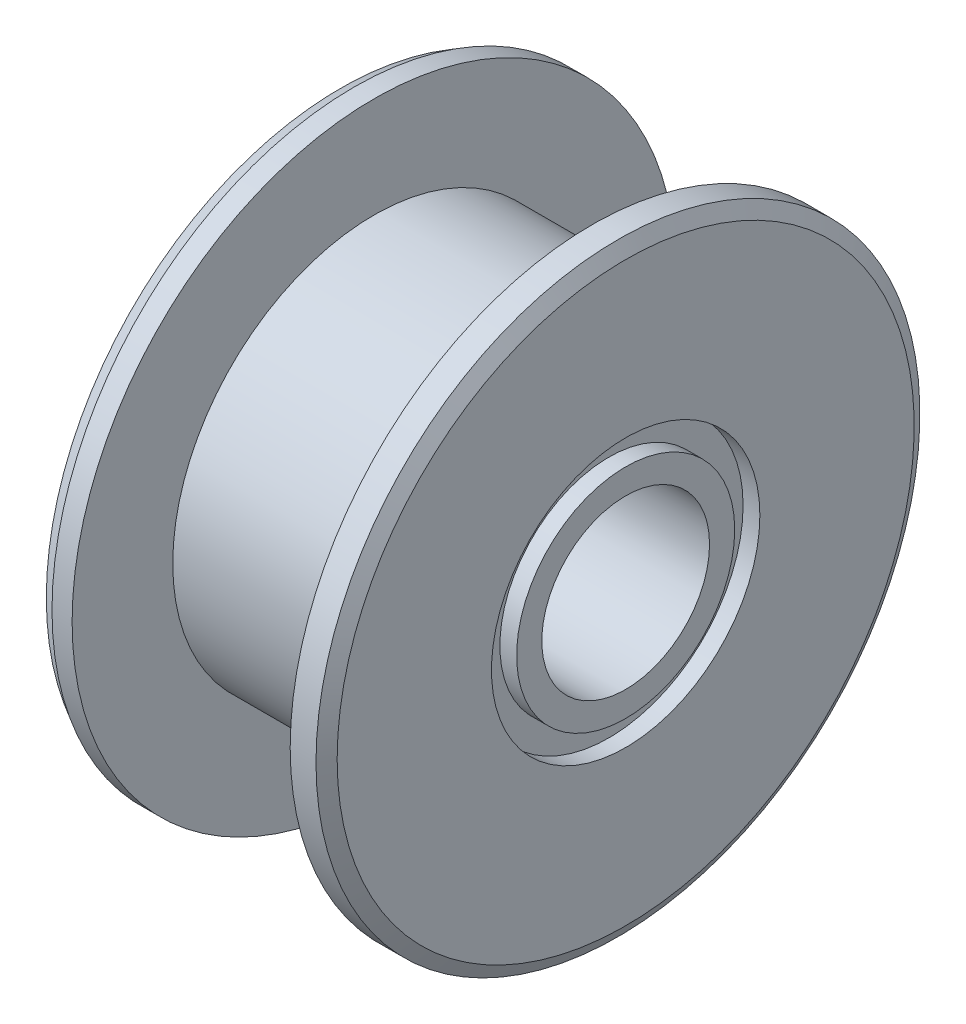
SolidWorks part; units mm, degrees
ref_plane "Front Plane" through (0, 0, 0) normal (0, 0, 1) x (1, 0, 0)
ref_plane "Top Plane" through (0, 0, 0) normal (0, 1, 0) x (1, 0, 0)
ref_plane "Right Plane" through (0, 0, 0) normal (1, 0, 0) x (0, 0, -1)
sketch "Sketch1" plane through (0, 0, 0) normal (0, 0, 1) x (1, 0, 0)
  line L0 (0, 0) -> (8.5, 0) construction
  line L1 (0, 0) -> (0, 9)
  line L2 (0, 9) -> (1, 9)
  line L3 (1, 9) -> (1, 6)
  line L4 (1, 6) -> (7.5, 6)
  line L5 (7.5, 6) -> (7.5, 9)
  line L6 (7.5, 9) -> (8.5, 9)
  line L7 (8.5, 9) -> (8.5, 0)
  line L8 (0, 0) -> (8.5, 0)
  dimension "D1" = 8.5
  dimension "D2" = 18
  dimension "D3" = 12
  dimension "D4" = 6.5
revolve "Revolve1" add sketch "Sketch1" angle 360 about L0
chamfer "Chamfer1" distance 0.4 angle 30 2 edges at (0, 0, 9) (8.5, 0, 9)
sketch "Sketch2" plane through (8.5, 0, 0) normal (1, 0, 0) x (0, 0, -1)
  circle A0 centre (0, 0) radius 2.5
  dimension "D1" = 5
extrude "Cut-Extrude1" cut sketch "Sketch2" against normal through all
sketch "Sketch3" plane through (8.5, 0, 0) normal (1, 0, 0) x (0, 0, -1)
  circle A0 centre (0, 0) radius 3.25
  circle A1 centre (0, 0) radius 4
  dimension "D1" = 8
  dimension "D2" = 6.5
extrude "Cut-Extrude2" cut sketch "Sketch3" against normal blind 0.5
sketch "Sketch4" plane through (0, 0, 0) normal (-1, 0, 0) x (0, 0, 1)
  circle A0 centre (0, 0) radius 3.25
  circle A1 centre (0, 0) radius 4
  dimension "D1" = 8
  dimension "D2" = 6.5
extrude "Cut-Extrude3" cut sketch "Sketch4" against normal blind 0.5
sketch "Sketch5" plane through (7.5, 0, 0) normal (-1, 0, 0) x (0, 0, 1)
  circle A0 centre (0, 0) radius 6 construction
  dimension "D1" = 12
